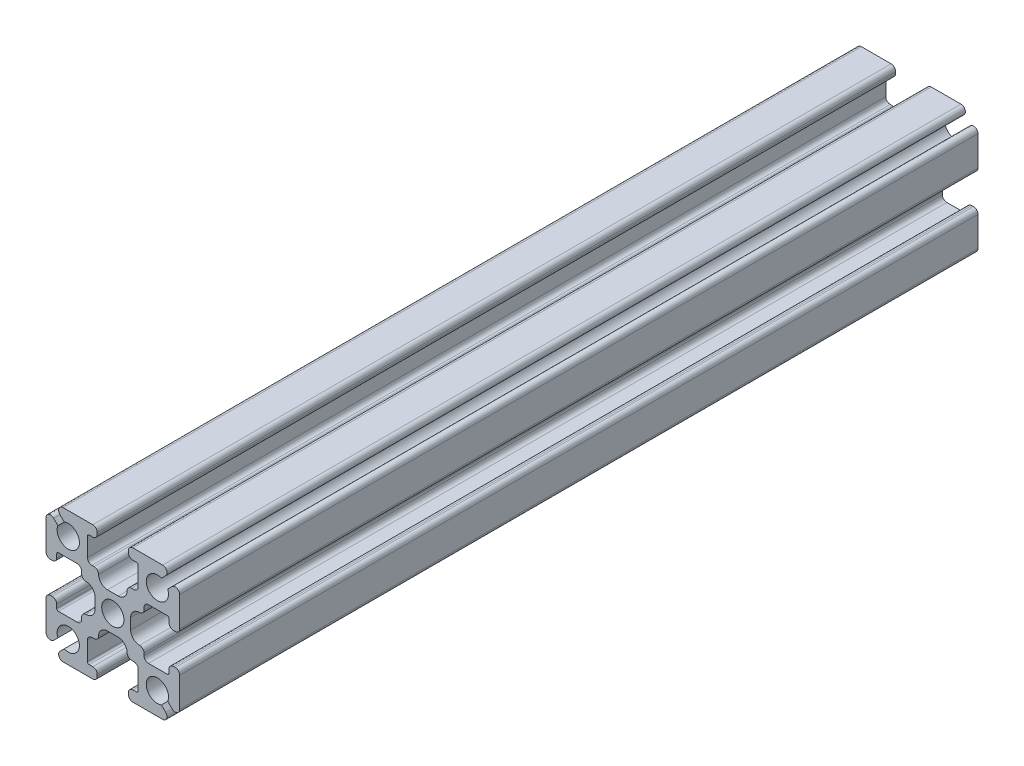
SolidWorks part; units mm, degrees
ref_plane "Front" through (0, 0, 0) normal (0, 0, 1) x (1, 0, 0)
ref_plane "Top" through (0, 0, 0) normal (0, 1, 0) x (1, 0, 0)
ref_plane "Right" through (0, 0, 0) normal (1, 0, 0) x (0, 0, -1)
sketch "Sketch1" plane through (0, 0, 0) normal (0, 0, 1) x (1, 0, 0)
  line L0 (6.6464, 5.9393) -> (6.1636, 5.4565)
  line L1 (5.4565, 6.1636) -> (5.9393, 6.6464)
  line L2 (5.5858, 7.5) -> (2.25, 7.5)
  line L3 (1.75, 7) -> (1.75, 6.8)
  line L4 (2.25, 6.3) -> (2.65, 6.3)
  line L5 (2.85, 6.1) -> (2.85, 4)
  line L6 (2.35, 3.5) -> (2.1, 3.5)
  line L7 (0.6, 2) -> (-0.6, 2)
  line L8 (-2.1, 3.5) -> (-2.35, 3.5)
  line L9 (-2.85, 4) -> (-2.85, 6.1)
  line L10 (-2.65, 6.3) -> (-2.25, 6.3)
  line L11 (-1.75, 6.8) -> (-1.75, 7)
  line L12 (-2.25, 7.5) -> (-5.5858, 7.5)
  line L13 (-5.9393, 6.6464) -> (-5.4565, 6.1636)
  line L14 (-6.1636, 5.4565) -> (-6.6464, 5.9393)
  line L15 (-7.5, 5.5858) -> (-7.5, 2.25)
  line L16 (-7, 1.75) -> (-6.8, 1.75)
  line L17 (-6.3, 2.25) -> (-6.3, 2.65)
  line L18 (-6.1, 2.85) -> (-4, 2.85)
  line L19 (-3.5, 2.35) -> (-3.5, 2.1)
  line L20 (-2, 0.6) -> (-2, -0.6)
  line L21 (-3.5, -2.1) -> (-3.5, -2.35)
  line L22 (-4, -2.85) -> (-6.1, -2.85)
  line L23 (-6.3, -2.65) -> (-6.3, -2.25)
  line L24 (-6.8, -1.75) -> (-7, -1.75)
  line L25 (-7.5, -2.25) -> (-7.5, -5.5858)
  line L26 (-6.6464, -5.9393) -> (-6.1636, -5.4565)
  line L27 (-5.4565, -6.1636) -> (-5.9393, -6.6464)
  line L28 (-5.5858, -7.5) -> (-2.25, -7.5)
  line L29 (-1.75, -7) -> (-1.75, -6.8)
  line L30 (-2.25, -6.3) -> (-2.65, -6.3)
  line L31 (-2.85, -6.1) -> (-2.85, -4)
  line L32 (-2.35, -3.5) -> (-2.1, -3.5)
  line L33 (-0.6, -2) -> (0.6, -2)
  line L34 (2.1, -3.5) -> (2.35, -3.5)
  line L35 (2.85, -4) -> (2.85, -6.1)
  line L36 (2.65, -6.3) -> (2.25, -6.3)
  line L37 (1.75, -6.8) -> (1.75, -7)
  line L38 (2.25, -7.5) -> (5.5858, -7.5)
  line L39 (5.9393, -6.6464) -> (5.4565, -6.1636)
  line L40 (6.1636, -5.4565) -> (6.6464, -5.9393)
  line L41 (7.5, -5.5858) -> (7.5, -2.25)
  line L42 (7, -1.75) -> (6.8, -1.75)
  line L43 (6.3, -2.25) -> (6.3, -2.65)
  line L44 (6.1, -2.85) -> (4, -2.85)
  line L45 (3.5, -2.35) -> (3.5, -2.1)
  line L46 (2, -0.6) -> (2, 0.6)
  line L47 (3.5, 2.1) -> (3.5, 2.35)
  line L48 (4, 2.85) -> (6.1, 2.85)
  line L49 (6.3, 2.65) -> (6.3, 2.25)
  line L50 (6.8, 1.75) -> (7, 1.75)
  line L51 (7.5, 2.25) -> (7.5, 5.5858)
  circle A0 centre (0, 0) radius 1.25
  arc A1 (6.1636, 5.4565) -> (5.4565, 6.1636) centre (5, 5) cw
  arc A2 (5.9393, 6.6464) -> (5.5858, 7.5) centre (5.5858, 7) ccw
  arc A3 (2.25, 7.5) -> (1.75, 7) centre (2.25, 7) ccw
  arc A4 (1.75, 6.8) -> (2.25, 6.3) centre (2.25, 6.8) ccw
  arc A5 (2.65, 6.3) -> (2.85, 6.1) centre (2.65, 6.1) cw
  arc A6 (2.85, 4) -> (2.35, 3.5) centre (2.35, 4) cw
  arc A7 (2.1, 3.5) -> (1.6, 3) centre (2.1, 3) ccw
  arc A8 (1.6, 3) -> (0.6, 2) centre (0.6, 3) cw
  arc A9 (-0.6, 2) -> (-1.6, 3) centre (-0.6, 3) cw
  arc A10 (-1.6, 3) -> (-2.1, 3.5) centre (-2.1, 3) ccw
  arc A11 (-2.35, 3.5) -> (-2.85, 4) centre (-2.35, 4) cw
  arc A12 (-2.85, 6.1) -> (-2.65, 6.3) centre (-2.65, 6.1) cw
  arc A13 (-2.25, 6.3) -> (-1.75, 6.8) centre (-2.25, 6.8) ccw
  arc A14 (-1.75, 7) -> (-2.25, 7.5) centre (-2.25, 7) ccw
  arc A15 (-5.5858, 7.5) -> (-5.9393, 6.6464) centre (-5.5858, 7) ccw
  arc A16 (-5.4565, 6.1636) -> (-6.1636, 5.4565) centre (-5, 5) cw
  arc A17 (-6.6464, 5.9393) -> (-7.5, 5.5858) centre (-7, 5.5858) ccw
  arc A18 (-7.5, 2.25) -> (-7, 1.75) centre (-7, 2.25) ccw
  arc A19 (-6.8, 1.75) -> (-6.3, 2.25) centre (-6.8, 2.25) ccw
  arc A20 (-6.3, 2.65) -> (-6.1, 2.85) centre (-6.1, 2.65) cw
  arc A21 (-4, 2.85) -> (-3.5, 2.35) centre (-4, 2.35) cw
  arc A22 (-3.5, 2.1) -> (-3, 1.6) centre (-3, 2.1) ccw
  arc A23 (-3, 1.6) -> (-2, 0.6) centre (-3, 0.6) cw
  arc A24 (-2, -0.6) -> (-3, -1.6) centre (-3, -0.6) cw
  arc A25 (-3, -1.6) -> (-3.5, -2.1) centre (-3, -2.1) ccw
  arc A26 (-3.5, -2.35) -> (-4, -2.85) centre (-4, -2.35) cw
  arc A27 (-6.1, -2.85) -> (-6.3, -2.65) centre (-6.1, -2.65) cw
  arc A28 (-6.3, -2.25) -> (-6.8, -1.75) centre (-6.8, -2.25) ccw
  arc A29 (-7, -1.75) -> (-7.5, -2.25) centre (-7, -2.25) ccw
  arc A30 (-7.5, -5.5858) -> (-6.6464, -5.9393) centre (-7, -5.5858) ccw
  arc A31 (-6.1636, -5.4565) -> (-5.4565, -6.1636) centre (-5, -5) cw
  arc A32 (-5.9393, -6.6464) -> (-5.5858, -7.5) centre (-5.5858, -7) ccw
  arc A33 (-2.25, -7.5) -> (-1.75, -7) centre (-2.25, -7) ccw
  arc A34 (-1.75, -6.8) -> (-2.25, -6.3) centre (-2.25, -6.8) ccw
  arc A35 (-2.65, -6.3) -> (-2.85, -6.1) centre (-2.65, -6.1) cw
  arc A36 (-2.85, -4) -> (-2.35, -3.5) centre (-2.35, -4) cw
  arc A37 (-2.1, -3.5) -> (-1.6, -3) centre (-2.1, -3) ccw
  arc A38 (-1.6, -3) -> (-0.6, -2) centre (-0.6, -3) cw
  arc A39 (0.6, -2) -> (1.6, -3) centre (0.6, -3) cw
  arc A40 (1.6, -3) -> (2.1, -3.5) centre (2.1, -3) ccw
  arc A41 (2.35, -3.5) -> (2.85, -4) centre (2.35, -4) cw
  arc A42 (2.85, -6.1) -> (2.65, -6.3) centre (2.65, -6.1) cw
  arc A43 (2.25, -6.3) -> (1.75, -6.8) centre (2.25, -6.8) ccw
  arc A44 (1.75, -7) -> (2.25, -7.5) centre (2.25, -7) ccw
  arc A45 (5.5858, -7.5) -> (5.9393, -6.6464) centre (5.5858, -7) ccw
  arc A46 (5.4565, -6.1636) -> (6.1636, -5.4565) centre (5, -5) cw
  arc A47 (6.6464, -5.9393) -> (7.5, -5.5858) centre (7, -5.5858) ccw
  arc A48 (7.5, -2.25) -> (7, -1.75) centre (7, -2.25) ccw
  arc A49 (6.8, -1.75) -> (6.3, -2.25) centre (6.8, -2.25) ccw
  arc A50 (6.3, -2.65) -> (6.1, -2.85) centre (6.1, -2.65) cw
  arc A51 (4, -2.85) -> (3.5, -2.35) centre (4, -2.35) cw
  arc A52 (3.5, -2.1) -> (3, -1.6) centre (3, -2.1) ccw
  arc A53 (3, -1.6) -> (2, -0.6) centre (3, -0.6) cw
  arc A54 (2, 0.6) -> (3, 1.6) centre (3, 0.6) cw
  arc A55 (3, 1.6) -> (3.5, 2.1) centre (3, 2.1) ccw
  arc A56 (3.5, 2.35) -> (4, 2.85) centre (4, 2.35) cw
  arc A57 (6.1, 2.85) -> (6.3, 2.65) centre (6.1, 2.65) cw
  arc A58 (6.3, 2.25) -> (6.8, 1.75) centre (6.8, 2.25) ccw
  arc A59 (7, 1.75) -> (7.5, 2.25) centre (7, 2.25) ccw
  arc A60 (7.5, 5.5858) -> (6.6464, 5.9393) centre (7, 5.5858) ccw
extrude "Boss-Extrude1" add sketch "Sketch1" along normal blind 89.6
